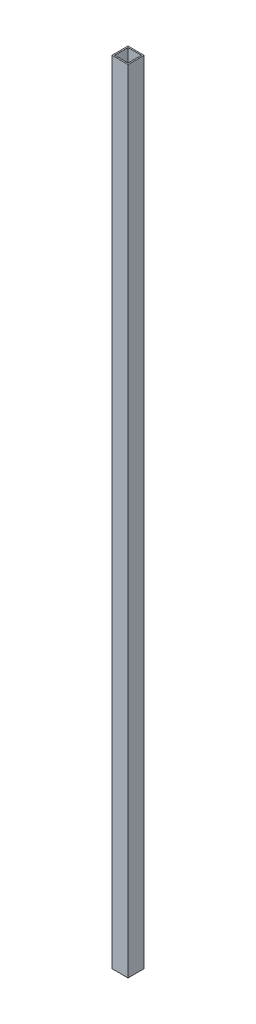
SolidWorks part; units mm, degrees
ref_plane "Front" through (0, 0, 0) normal (0, 0, 1) x (1, 0, 0)
ref_plane "Top" through (0, 0, 0) normal (0, 1, 0) x (1, 0, 0)
ref_plane "Right" through (0, 0, 0) normal (1, 0, 0) x (0, 0, -1)
sketch "Sketch1" plane through (0, 0, 0) normal (0, 1, 0) x (1, 0, 0)
  line L1 (0, 0) -> (19.05, 0)
  line L2 (0, 0) -> (0, 19.05)
  line L3 (0, 19.05) -> (19.05, 19.05)
  line L4 (19.05, 0) -> (19.05, 19.05)
  line L5 (0, 0) -> (19.05, 19.05) construction
  line L6 (0, 19.05) -> (19.05, 0) construction
  line L7 (1.5875, 1.5875) -> (17.4625, 1.5875)
  line L8 (1.5875, 1.5875) -> (1.5875, 17.4625)
  line L9 (1.5875, 17.4625) -> (17.4625, 17.4625)
  line L10 (17.4625, 1.5875) -> (17.4625, 17.4625)
  line L11 (1.5875, 1.5875) -> (17.4625, 17.4625) construction
  line L12 (1.5875, 17.4625) -> (17.4625, 1.5875) construction
  point P4 (9.525, 9.525)
  point P5 (9.525, 9.525)
  dimension "D1" = 1.5875
  dimension "D2" = 1.5875
  dimension "D3" = 19.05
extrude "Boss-Extrude1" add sketch "Sketch1" along normal blind 939.8
